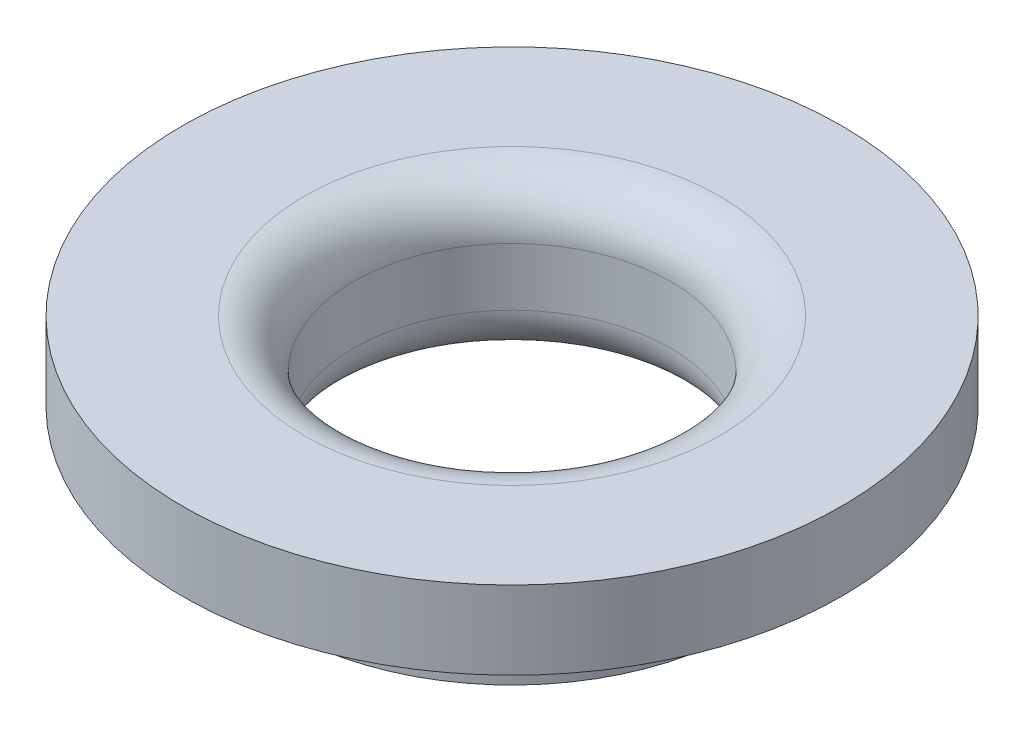
SolidWorks part; units mm, degrees
ref_plane "Front" through (0, 0, 0) normal (0, 0, 1) x (1, 0, 0)
ref_plane "Top" through (0, 0, 0) normal (0, 1, 0) x (1, 0, 0)
ref_plane "Right" through (0, 0, 0) normal (1, 0, 0) x (0, 0, -1)
sketch "Sketch2" plane through (0, 0, 0) normal (0, 0, 1) x (1, 0, 0)
  line L0 (-6.699, 3.175) -> (-3.22, 3.175)
  line L1 (-3.22, 3.175) -> (-3.22, 0)
  line L2 (-3.22, 0) -> (-4.699, 0)
  line L3 (-4.699, 0) -> (-4.699, 1.5875)
  line L5 (-6.699, 3.175) -> (-6.699, 1.5875)
  line L6 (-6.699, 1.5875) -> (-4.699, 1.5875)
  line L7 (-4.699, 1.5875) -> (-6.699, 1.5875)
  line L8 (0, 0) -> (0, 22.7763) construction
  dimension "D1" = 2
  dimension "D2" = 1.5875
  dimension "D3" = 3.22
  dimension "D4" = 1.5875
  dimension "D5" = 9.398
revolve "Revolve1" add sketch "Sketch2" angle 360 about L8
fillet "Fillet1" radius 1 2 edges at (0, 3.175, -3.22) (0, 0, -3.22)
sketch "Sketch3" plane through (0, 1.5875, 0) normal (0, -1, 0) x (1, 0, 0)
  line L0 (-0.3, 4.6894) -> (-0.2285, 4.8505)
  line L1 (0.2285, 4.8505) -> (0.3, 4.6894)
  line L2 (3.9112, 2.6045) -> (4.0864, 2.6231)
  line L3 (0, 4.999) -> (0, 0) construction
  line L4 (4.3149, 2.2274) -> (4.2112, 2.0849)
  line L5 (4.2112, -2.0849) -> (4.3149, -2.2274)
  line L6 (4.0864, -2.6231) -> (3.9112, -2.6045)
  line L7 (0.3, -4.6894) -> (0.2285, -4.8505)
  line L8 (-0.2285, -4.8505) -> (-0.3, -4.6894)
  line L9 (-3.9112, -2.6045) -> (-4.0864, -2.6231)
  line L10 (-4.3149, -2.2274) -> (-4.2112, -2.0849)
  line L11 (-4.2112, 2.0849) -> (-4.3149, 2.2274)
  line L12 (-4.0864, 2.6231) -> (-3.9112, 2.6045)
  circle A0 centre (0, 0) radius 4.699
  arc A1 (0.2285, 4.8505) -> (-0.2285, 4.8505) centre (0, 4.749) ccw
  arc A2 (4.3149, 2.2274) -> (4.0864, 2.6231) centre (4.1128, 2.3745) ccw
  arc A3 (4.0864, -2.6231) -> (4.3149, -2.2274) centre (4.1128, -2.3745) ccw
  arc A4 (-0.2285, -4.8505) -> (0.2285, -4.8505) centre (0, -4.749) ccw
  arc A5 (-4.3149, -2.2274) -> (-4.0864, -2.6231) centre (-4.1128, -2.3745) ccw
  arc A6 (-4.0864, 2.6231) -> (-4.3149, 2.2274) centre (-4.1128, 2.3745) ccw
  point P9 (0, 5.199)
  point P10 (0, 4.699)
  point P12 (0, 5.365)
  point P51 (0, 0)
  dimension "D1" = 0.25
  dimension "D2" = 0.3
  dimension "D3" = 0.6
  dimension "D4" = 6
extrude "Boss-Extrude1" [suppressed] add sketch "Sketch3" along normal up to surface (1.5875 mm away) contours L4 A2 L2 L12 | A1 L3 A0 L1 | L3 A1 L0 L12 | L12 A6 L11 | L10 A5 L9 L12 | L6 A3 L5 L12 | L8 A4 L7 L12
sketch "Sketch5" [suppressed] plane through (0, 0, 0) normal (1, 0, 0) x (0, 0, -1)
  line L2 (-4.7, 3.6194) -> (-4.7, 3.8694)
  line L3 (-4.999, 1.5875) -> (-4.999, 0) construction
  line L4 (-4.999, 0.7149) -> (-4.999, 0.3322) construction
  line L5 (-4.999, 4.0829) -> (-5.3256, 4.0829)
  line L6 (-5.3256, 4.0829) -> (-5.3256, 3.3485)
  line L7 (-5.3256, 3.3485) -> (-4.7, 3.3485)
  line L8 (-4.7, 3.3485) -> (-4.7, 3.6194)
  line L9 (0, 0) -> (0, 7.9892) construction
  spline S0 degree 2 poles (-4.7, 3.8694) (-4.999, 3.8728) (-4.999, 4.0829) knots 0 0 0 1 1 1
  dimension "D1" = 0.25
  dimension "D2" = 4.7
revolve "Cut-Revolve1" [suppressed] cut sketch "Sketch5" angle 360 about L9
